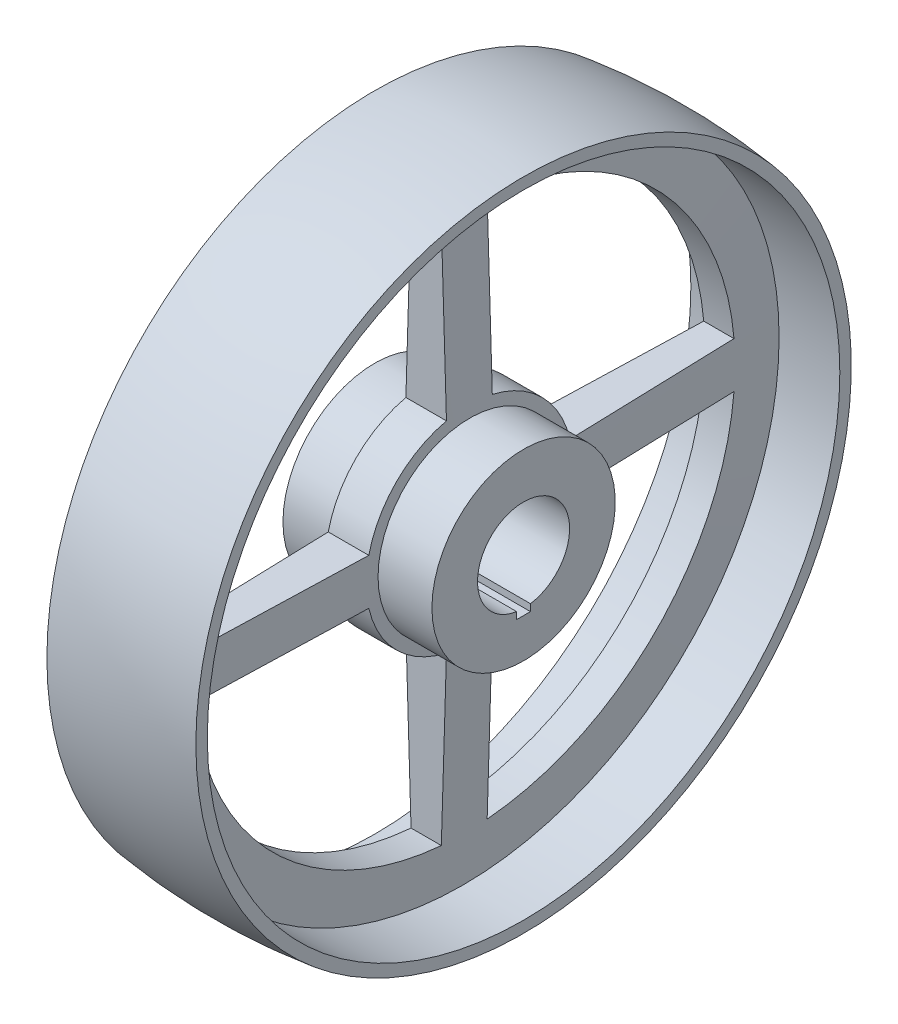
SolidWorks part; units mm, degrees
ref_plane "Front Plane" through (0, 0, 0) normal (0, 0, 1) x (1, 0, 0)
ref_plane "Top Plane" through (0, 0, 0) normal (0, 1, 0) x (1, 0, 0)
ref_plane "Right Plane" through (0, 0, 0) normal (1, 0, 0) x (0, 0, -1)
sketch "Sketch2" plane through (0, 0, 0) normal (0, 0, 1) x (1, 0, 0)
  line L1 (32.5, 20) -> (32.5, 40)
  line L2 (32.5, 40) -> (9, 40)
  line L4 (-9, 40) -> (-32.5, 40)
  line L5 (-32.5, 40) -> (-32.5, 20)
  line L6 (-32.5, 20) -> (32.5, 20)
  line L10 (-32.5, 143) -> (-32.5, 138)
  line L11 (-32.5, 138) -> (-6, 138)
  line L13 (6, 138) -> (32.5, 138)
  line L14 (32.5, 138) -> (32.5, 143)
  line L15 (0, 15.5326) -> (0, -35.2546) construction
  line L16 (-129.9399, 0) -> (143.8147, 0) construction
  line L17 (9, 81.5039) -> (9, 40) construction
  line L18 (-9, 81.5039) -> (-9, 40) construction
  line L19 (-6, 138) -> (-6, 99.7261) construction
  line L20 (9, 40) -> (6, 138)
  line L21 (6, 99.7261) -> (6, 138) construction
  line L22 (-9, 40) -> (-6, 138)
  arc A0 (9, 40) -> (-9, 40) centre (0, 40) ccw
  arc A1 (6, 138) -> (-6, 138) centre (0, 138) cw
  arc A2 (-32.5, 143) -> (32.5, 143) centre (0, -120.0625) cw
  point P15 (0, 145)
  dimension "D2" = 40
  dimension "D4" = 138
  dimension "D1" = 65
  dimension "D3" = 145
  dimension "D6" = 20
  dimension "D8" = 5
  dimension "D11" = 18
  dimension "D12" = 12
revolve "Revolve2" add sketch "Sketch2" angle 360 about L16
sketch "Sketch3" plane through (0, 0, 0) normal (1, 0, 0) x (0, 0, -1)
  line L0 (0, 175.1798) -> (0, -167.6227) construction
  line L1 (-174.5575, 0) -> (167.5014, 0) construction
  line L2 (10, 117.7141) -> (10, 43.8748)
  line L3 (-10, 117.7141) -> (-10, 43.8748)
  line L4 (117.7141, -10) -> (43.8748, -10)
  line L5 (117.7141, 10) -> (43.8748, 10)
  line L6 (-10, -117.7141) -> (-10, -43.8748)
  line L7 (10, -117.7141) -> (10, -43.8748)
  line L8 (-117.7141, 10) -> (-43.8748, 10)
  line L9 (-117.7141, -10) -> (-43.8748, -10)
  arc A0 (-10, 117.7141) -> (-117.7141, 10) centre (0, 0) ccw
  arc A1 (-10, 43.8748) -> (-43.8748, 10) centre (0, 0) ccw
  arc A2 (43.8748, 10) -> (10, 43.8748) centre (0, 0) ccw
  arc A3 (-43.8748, -10) -> (-10, -43.8748) centre (0, 0) ccw
  arc A4 (10, -43.8748) -> (43.8748, -10) centre (0, 0) ccw
  arc A5 (117.7141, 10) -> (10, 117.7141) centre (0, 0) ccw
  arc A6 (-117.7141, -10) -> (-10, -117.7141) centre (0, 0) ccw
  arc A7 (10, -117.7141) -> (117.7141, -10) centre (0, 0) ccw
  point P26 (0, 0)
  dimension "D1" = 20
  dimension "D3" = 118.1381
  dimension "D4" = 45
  dimension "D2" = 4
extrude "Cut-Extrude4" cut sketch "Sketch3" against normal through all both and the other way through all contours L2 A2 L5 A5 | L3 A1 L8 A0 | L9 A3 L6 A6 | A7 L4 A4 L7
sketch "Sketch4" plane through (32.5, 0, 0) normal (1, 0, 0) x (0, 0, -1)
  line L0 (0, 102.6621) -> (0, -57.3308) construction
  line L1 (-87.9961, 0) -> (80.4409, 0) construction
  line L2 (3, -19.8663) -> (3, -22.8663)
  line L3 (3, -22.8663) -> (-3, -22.8663)
  line L4 (-3, -22.8663) -> (-3, -19.8663)
  arc A1 (3, -19.8663) -> (-3, -19.8663) centre (0, 0) ccw
  dimension "D1" = 6
  dimension "D2" = 3
extrude "Cut-Extrude5" cut sketch "Sketch4" against normal through all both
